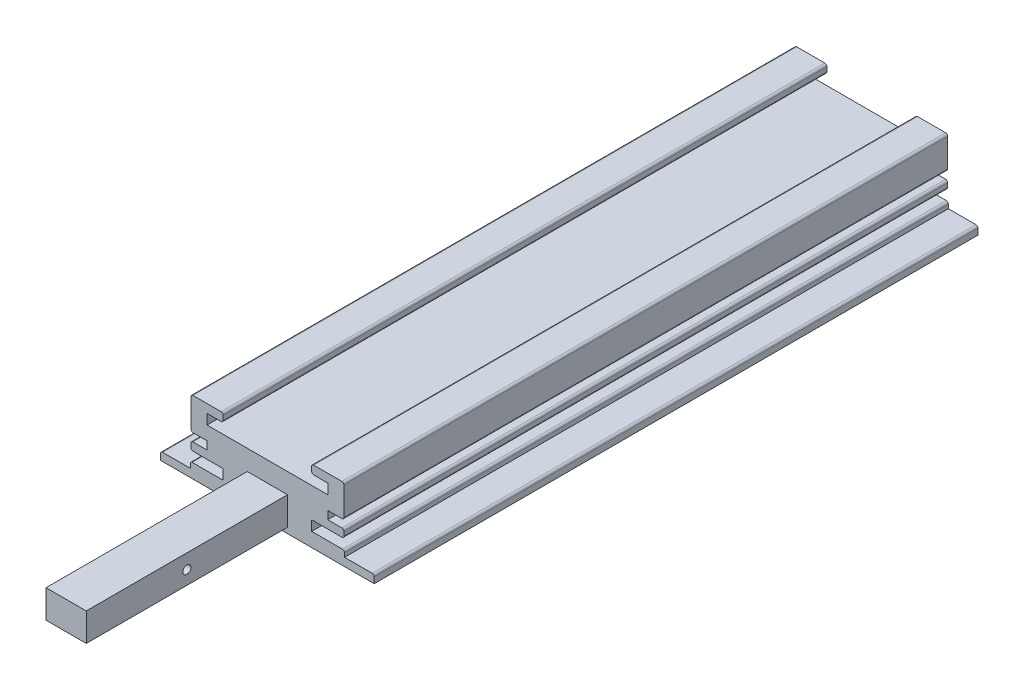
SolidWorks part; units mm, degrees
ref_plane "Front Plane" through (0, 0, 0) normal (0, 0, 1) x (1, 0, 0)
ref_plane "Top Plane" through (0, 0, 0) normal (0, 1, 0) x (1, 0, 0)
ref_plane "Right Plane" through (0, 0, 0) normal (1, 0, 0) x (0, 0, -1)
sketch "Sketch1" plane through (0, 0, 0) normal (0, 0, 1) x (1, 0, 0)
  line L0 (0, 27.8778) -> (0, -24.7586) construction
  line L1 (-15, 12.9127) -> (15, 12.9127)
  line L2 (15, 12.9127) -> (15, 15.4127)
  line L3 (-15, 12.9127) -> (-15, 15.4127)
  line L4 (15, 15.4127) -> (11.5, 15.4127)
  line L5 (-15, 15.4127) -> (-11.5, 15.4127)
  line L6 (11, 15.9127) -> (11, 17.0286)
  line L7 (-11, 15.9127) -> (-11, 17.0286)
  line L8 (11.5, 17.5286) -> (18.5, 17.5286)
  line L9 (-11.5, 17.5286) -> (-18.5, 17.5286)
  line L10 (19, 17.0286) -> (19, 10.0286)
  line L11 (-19, 17.0286) -> (-19, 10.0286)
  line L12 (18.5, 9.5286) -> (15, 9.5286)
  line L13 (-18.5, 9.5286) -> (-15, 9.5286)
  line L14 (15, 9.5286) -> (15, 7.5286)
  line L15 (-15, 9.5286) -> (-15, 7.5286)
  line L16 (15, 7.5286) -> (18.5, 7.5286)
  line L17 (-15, 7.5286) -> (-18.5, 7.5286)
  line L18 (19, 7.0286) -> (19, 6.0286)
  line L19 (-19, 7.0286) -> (-19, 6.0286)
  line L20 (18.5, 5.5286) -> (11, 5.5286)
  line L21 (-18.5, 5.5286) -> (-11, 5.5286)
  line L22 (11, 5.5286) -> (11, 3.0286)
  line L23 (-11, 5.5286) -> (-11, 3.0286)
  line L24 (11, 3.0286) -> (18.6612, 3.0286)
  line L25 (-11, 3.0286) -> (-18.6612, 3.0286)
  line L26 (19.1612, 2.5286) -> (19.1612, 1.5286)
  line L27 (-19.1612, 2.5286) -> (-19.1612, 1.5286)
  line L28 (19.1612, 1.5286) -> (26.0293, 1.5286)
  line L29 (-19.1612, 1.5286) -> (-26.0293, 1.5286)
  line L30 (26.5293, 1.0286) -> (26.5293, -0.4714)
  line L31 (-26.5293, 1.0286) -> (-26.5293, -0.4714)
  line L32 (26.5293, -0.4714) -> (11.0705, -0.4714)
  line L33 (-26.5293, -0.4714) -> (-11.0705, -0.4714)
  line L34 (11.0705, -0.4714) -> (-11.0705, -0.4714)
  arc A0 (-26.0293, 1.5286) -> (-26.5293, 1.0286) centre (-26.0293, 1.0286) ccw
  arc A1 (-18.6612, 3.0286) -> (-19.1612, 2.5286) centre (-18.6612, 2.5286) ccw
  arc A2 (-19, 6.0286) -> (-18.5, 5.5286) centre (-18.5, 6.0286) ccw
  arc A3 (-18.5, 7.5286) -> (-19, 7.0286) centre (-18.5, 7.0286) ccw
  arc A4 (-19, 10.0286) -> (-18.5, 9.5286) centre (-18.5, 10.0286) ccw
  arc A5 (-18.5, 17.5286) -> (-19, 17.0286) centre (-18.5, 17.0286) ccw
  arc A6 (-11.5, 15.4127) -> (-11, 15.9127) centre (-11.5, 15.9127) ccw
  arc A7 (-11, 17.0286) -> (-11.5, 17.5286) centre (-11.5, 17.0286) ccw
  arc A8 (26.0293, 1.5286) -> (26.5293, 1.0286) centre (26.0293, 1.0286) cw
  arc A9 (18.6612, 3.0286) -> (19.1612, 2.5286) centre (18.6612, 2.5286) cw
  arc A10 (19, 6.0286) -> (18.5, 5.5286) centre (18.5, 6.0286) cw
  arc A11 (18.5, 7.5286) -> (19, 7.0286) centre (18.5, 7.0286) cw
  arc A12 (19, 10.0286) -> (18.5, 9.5286) centre (18.5, 10.0286) cw
  arc A13 (18.5, 17.5286) -> (19, 17.0286) centre (18.5, 17.0286) cw
  arc A14 (11.5, 15.4127) -> (11, 15.9127) centre (11.5, 15.9127) cw
  arc A15 (11, 17.0286) -> (11.5, 17.5286) centre (11.5, 17.0286) cw
  point P6 (0, 12.9127)
  point P39 (0, -0.4714)
  point P41 (-26.5293, 1.5286)
  point P44 (-19.1612, 3.0286)
  point P47 (-19, 5.5286)
  point P50 (-19, 7.5286)
  point P53 (-19, 9.5286)
  point P56 (-19, 17.5286)
  point P59 (-11, 15.4127)
  point P62 (-11, 17.5286)
  point P65 (26.5293, 1.5286)
  point P68 (19.1612, 3.0286)
  point P71 (19, 5.5286)
  point P74 (19, 7.5286)
  point P77 (19, 9.5286)
  point P80 (19, 17.5286)
  point P83 (11, 15.4127)
  point P86 (11, 17.5286)
  dimension "D14" = 0.5
  dimension "D1" = 30
  dimension "D2" = 2.5
  dimension "D3" = 4
  dimension "D4" = 8
  dimension "D5" = 2
  dimension "D6" = 4
  dimension "D7" = 8
  dimension "D8" = 19
  dimension "D9" = 2.5
  dimension "D10" = 8
  dimension "D11" = 2
  dimension "D12" = 1.5
  dimension "D13" = 2
extrude "Boss-Extrude1" add sketch "Sketch1" along normal blind 150
sketch "Sketch2" plane through (0, 0, 150) normal (0, 0, 1) x (1, 0, 0)
  line L0 (15, 12.9127) -> (-15, 12.9127) construction
  line L1 (-5, 7.9127) -> (5, 7.9127)
  line L2 (-5, 7.9127) -> (-5, 0.9127)
  line L3 (-5, 0.9127) -> (5, 0.9127)
  line L4 (5, 7.9127) -> (5, 0.9127)
  line L5 (-15, 12.9127) -> (-15, 15.4127) construction
  line L6 (15, 15.4127) -> (15, 12.9127) construction
  line L8 (-18.5, 5.5286) -> (-11, 5.5286) construction
  point P8 (-15, 14.1627)
  dimension "D1" = 5
  dimension "D2" = 7
  dimension "D3" = 10
  dimension "D4" = 10
  dimension "D5" = 2.3841
extrude "Boss-Extrude4" add sketch "Sketch2" along normal blind 50
sketch "Sketch4" plane through (5, 0, 0) normal (1, 0, 0) x (0, 0, -1)
  line L0 (-200, 7.9127) -> (-150, 7.9127) construction
  line L1 (-200, 0.9127) -> (-200, 7.9127) construction
  circle A0 centre (-175, 4.2827) radius 1
  dimension "D1" = 3.63
  dimension "D2" = 25
extrude "Cut-Extrude2" cut sketch "Sketch4" against normal blind 50
sketch "Sketch5" plane through (0, 0, 0) normal (0, 0, -1) x (-1, 0, 0)
  line L0 (-15, 15.4127) -> (-15, 12.9127) construction
  line L1 (-5, 7.9127) -> (5, 7.9127)
  line L2 (-5, 7.9127) -> (-5, 0.9127)
  line L3 (-5, 0.9127) -> (5, 0.9127)
  line L4 (5, 7.9127) -> (5, 0.9127)
  line L5 (15, 12.9127) -> (15, 15.4127) construction
  line L6 (-15, 12.9127) -> (15, 12.9127) construction
  dimension "D1" = 7
  dimension "D2" = 10
  dimension "D3" = 10
  dimension "D4" = 5
extrude "Cut-Extrude3" cut sketch "Sketch5" against normal blind 50
sketch "Sketch6" plane through (-11, 0, 0) normal (-1, 0, 0) x (0, 0, 1)
  line L0 (0, 5.5286) -> (0, 3.0286) construction
  line L1 (150, 3.0286) -> (0, 3.0286) construction
  circle A0 centre (25, 4.2786) radius 1
  point P4 (0, 0)
  dimension "D1" = 25
  dimension "D2" = 1.25
extrude "Cut-Extrude4" cut sketch "Sketch6" against normal blind 100
